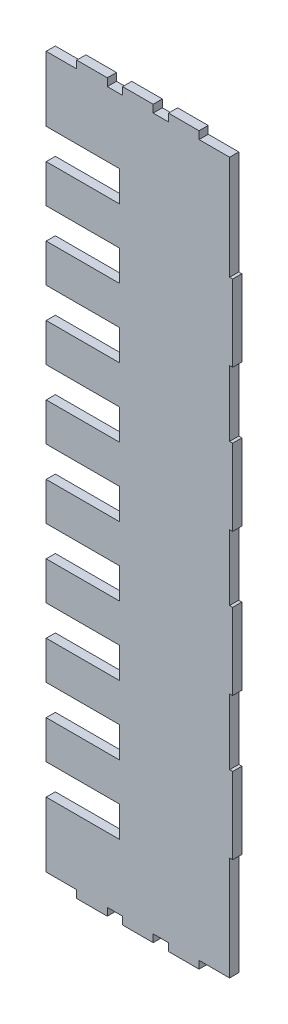
SolidWorks part; units mm, degrees
ref_plane "Front Plane" through (0, 0, 0) normal (0, 0, 1) x (1, 0, 0)
ref_plane "Top Plane" through (0, 0, 0) normal (0, 1, 0) x (1, 0, 0)
ref_plane "Right Plane" through (0, 0, 0) normal (1, 0, 0) x (0, 0, -1)
sketch "Sketch1" plane through (0, 0, 0) normal (0, 0, 1) x (1, 0, 0)
  line L1 (-60, -232.5) -> (60, -232.5)
  line L2 (-60, -232.5) -> (-60, 232.5)
  line L3 (-60, 232.5) -> (60, 232.5)
  line L4 (60, -232.5) -> (60, 232.5)
  line L5 (0, 232.5) -> (0, -232.5) construction
  line L6 (-60, 0) -> (60, 0) construction
  point P0 (0, 0)
  dimension "D1" = 465
  dimension "D2" = 120
extrude "Boss-Extrude1" add sketch "Sketch1" along normal blind 6
sketch "Sketch2" plane through (0, 0, 6) normal (0, 0, 1) x (1, 0, 0)
  line L0 (-60, -232.5) -> (60, -232.5) construction
  line L1 (-60, 232.5) -> (-42, 232.5)
  line L2 (-60, 232.5) -> (-60, -232.5)
  line L3 (-60, -232.5) -> (-42, -232.5)
  line L4 (-42, 232.5) -> (-42, -232.5)
  line L5 (-42, 232.5) -> (-42, 180)
  line L6 (-42, 190) -> (-42, 170)
  line L7 (-42, 170) -> (-42, 135)
  line L8 (-42, 190) -> (-12, 190)
  line L9 (-42, 190) -> (-42, 170)
  line L10 (-42, 170) -> (-12, 170)
  line L11 (-12, 190) -> (-12, 170)
  line L12 (-42, 145) -> (-42, 125)
  line L13 (-42, 100) -> (-42, 80)
  line L14 (-42, 55) -> (-42, 35)
  line L15 (-42, 10) -> (-42, -10)
  line L16 (-42, -35) -> (-42, -55)
  line L17 (-42, -80) -> (-42, -100)
  line L18 (-42, -125) -> (-42, -145)
  line L19 (-42, -170) -> (-42, -190)
  line L21 (-42, 145) -> (-12, 145)
  line L22 (-42, 145) -> (-42, 125)
  line L23 (-42, 125) -> (-12, 125)
  line L24 (-12, 145) -> (-12, 125)
  line L25 (-42, 100) -> (-12, 100)
  line L26 (-42, 100) -> (-42, 80)
  line L27 (-42, 80) -> (-12, 80)
  line L28 (-12, 100) -> (-12, 80)
  line L29 (-42, 55) -> (-12, 55)
  line L30 (-42, 55) -> (-42, 35)
  line L31 (-42, 35) -> (-12, 35)
  line L32 (-12, 55) -> (-12, 35)
  line L33 (-42, 10) -> (-12, 10)
  line L34 (-42, 10) -> (-42, -10)
  line L35 (-42, -10) -> (-12, -10)
  line L36 (-12, 10) -> (-12, -10)
  line L37 (-42, -35) -> (-12, -35)
  line L38 (-42, -35) -> (-42, -55)
  line L39 (-42, -55) -> (-12, -55)
  line L40 (-12, -35) -> (-12, -55)
  line L41 (-42, -80) -> (-12, -80)
  line L42 (-42, -80) -> (-42, -100)
  line L43 (-42, -100) -> (-12, -100)
  line L44 (-12, -80) -> (-12, -100)
  line L45 (-42, -125) -> (-12, -125)
  line L46 (-42, -125) -> (-42, -145)
  line L47 (-42, -145) -> (-12, -145)
  line L48 (-12, -125) -> (-12, -145)
  line L49 (-42, -170) -> (-12, -170)
  line L50 (-42, -170) -> (-42, -190)
  line L51 (-42, -190) -> (-12, -190)
  line L52 (-12, -170) -> (-12, -190)
  point P9 (-42, 180)
  point P12 (-42, 90)
  point P14 (-42, 45)
  point P15 (-42, 0)
  point P16 (-42, -45)
  point P17 (-42, -90)
  point P18 (-42, -135)
  point P19 (-42, -180)
  point P20 (-42, -232.5)
  point P24 (-42, 135)
  point P27 (-42, 90)
  point P30 (-42, 45)
  point P33 (-42, 0)
  point P36 (-42, -45)
  point P39 (-42, -90)
  point P42 (-42, -135)
  point P45 (-42, -180)
  dimension "D1" = 465
  dimension "D2" = 18
  dimension "D3" = 52.5
  dimension "D4" = 20
  dimension "D5" = 30
  dimension "D6" = 45
  dimension "D7" = 45
  dimension "D8" = 45
  dimension "D9" = 45
  dimension "D10" = 45
  dimension "D11" = 45
  dimension "D12" = 45
  dimension "D13" = 45
  dimension "D14" = 52.5
  dimension "D15" = 20
  dimension "D16" = 20
  dimension "D17" = 20
  dimension "D18" = 20
  dimension "D19" = 20
  dimension "D20" = 20
  dimension "D21" = 20
  dimension "D22" = 20
extrude "Cut-Extrude1" cut sketch "Sketch2" against normal blind 8 contours L11 L8 L5 L4 L10 | L24 L21 L7 L4 L23 | L28 L25 L4 L27 | L32 L29 L4 L31 | L36 L33 L4 L35 | L40 L37 L4 L39 | L44 L41 L4 L43 | L48 L45 L4 L47 | L52 L49 L4 L51
sketch "Sketch4" plane through (0, 0, 6) normal (0, 0, 1) x (1, 0, 0)
  line L0 (60, 232.5) -> (-60, 232.5) construction
  line L1 (-40, 237.5) -> (-20, 237.5)
  line L2 (-40, 237.5) -> (-40, 227.5)
  line L3 (-40, 227.5) -> (-20, 227.5)
  line L4 (-20, 237.5) -> (-20, 227.5)
  line L5 (-30, 227.5) -> (-30, 237.5) construction
  line L6 (-40, 232.5) -> (-20, 232.5) construction
  line L7 (-60, -232.5) -> (60, -232.5) construction
  line L8 (-10, 237.5) -> (10, 237.5)
  line L9 (-10, 237.5) -> (-10, 227.5)
  line L10 (-10, 227.5) -> (10, 227.5)
  line L11 (10, 237.5) -> (10, 227.5)
  line L12 (0, 227.5) -> (0, 237.5) construction
  line L13 (-10, 232.5) -> (10, 232.5) construction
  line L14 (40, 237.5) -> (20, 237.5)
  line L15 (40, 237.5) -> (40, 227.5)
  line L16 (40, 227.5) -> (20, 227.5)
  line L17 (20, 237.5) -> (20, 227.5)
  line L18 (30, 227.5) -> (30, 237.5) construction
  line L19 (40, 232.5) -> (20, 232.5) construction
  line L20 (-40, -227.5) -> (-20, -227.5)
  line L21 (-40, -227.5) -> (-40, -237.5)
  line L22 (-40, -237.5) -> (-20, -237.5)
  line L23 (-20, -227.5) -> (-20, -237.5)
  line L24 (-30, -237.5) -> (-30, -227.5) construction
  line L25 (-40, -232.5) -> (-20, -232.5) construction
  line L26 (60, -232.5) -> (60, 232.5) construction
  line L27 (-10, -227.5) -> (10, -227.5)
  line L28 (-10, -227.5) -> (-10, -237.5)
  line L29 (-10, -237.5) -> (10, -237.5)
  line L30 (10, -227.5) -> (10, -237.5)
  line L31 (0, -237.5) -> (0, -227.5) construction
  line L32 (-10, -232.5) -> (10, -232.5) construction
  line L33 (20, -227.5) -> (40, -227.5)
  line L34 (20, -227.5) -> (20, -237.5)
  line L35 (20, -237.5) -> (40, -237.5)
  line L36 (40, -227.5) -> (40, -237.5)
  line L37 (30, -237.5) -> (30, -227.5) construction
  line L38 (20, -232.5) -> (40, -232.5) construction
  line L39 (58, 164.5) -> (62, 164.5)
  line L40 (58, 164.5) -> (58, 114.5)
  line L41 (58, 114.5) -> (62, 114.5)
  line L42 (62, 164.5) -> (62, 114.5)
  line L43 (60, 114.5) -> (60, 164.5) construction
  line L44 (58, 139.5) -> (62, 139.5) construction
  line L46 (58, 71.5) -> (62, 71.5)
  line L47 (58, 71.5) -> (58, 21.5)
  line L48 (58, 21.5) -> (62, 21.5)
  line L49 (62, 71.5) -> (62, 21.5)
  line L50 (60, 21.5) -> (60, 71.5) construction
  line L51 (58, 46.5) -> (62, 46.5) construction
  line L52 (58, -71.5) -> (62, -71.5)
  line L53 (58, -71.5) -> (58, -21.5)
  line L54 (58, -21.5) -> (62, -21.5)
  line L55 (62, -71.5) -> (62, -21.5)
  line L56 (60, -21.5) -> (60, -71.5) construction
  line L57 (58, -46.5) -> (62, -46.5) construction
  line L58 (58, -114.5) -> (62, -114.5)
  line L59 (58, -114.5) -> (58, -164.5)
  line L60 (58, -164.5) -> (62, -164.5)
  line L61 (62, -114.5) -> (62, -164.5)
  line L62 (60, -164.5) -> (60, -114.5) construction
  line L63 (58, -139.5) -> (62, -139.5) construction
  point P0 (-30, 232.5)
  point P6 (0, 232.5)
  point P10 (30, 232.5)
  point P14 (-30, -232.5)
  point P20 (0, -232.5)
  point P24 (30, -232.5)
  point P28 (60, 139.5)
  point P34 (60, 46.5)
  point P38 (60, -46.5)
  point P42 (60, -139.5)
  dimension "D1" = 30
  dimension "D2" = 60
  dimension "D3" = 90
  dimension "D4" = 20
  dimension "D5" = 20
  dimension "D6" = 20
  dimension "D7" = 10
  dimension "D8" = 10
  dimension "D9" = 10
  dimension "D10" = 30
  dimension "D11" = 60
  dimension "D12" = 90
  dimension "D13" = 20
  dimension "D14" = 20
  dimension "D15" = 20
  dimension "D16" = 10
  dimension "D17" = 10
  dimension "D18" = 10
  dimension "D19" = 93
  dimension "D20" = 93
  dimension "D21" = 93
  dimension "D22" = 93
  dimension "D23" = 4
  dimension "D24" = 4
  dimension "D25" = 4
  dimension "D26" = 4
  dimension "D27" = 50
  dimension "D28" = 50
  dimension "D29" = 50
  dimension "D30" = 50
extrude "Boss-Extrude2" add sketch "Sketch4" against normal blind 6
sketch "Sketch5" plane through (0, 0, 6) normal (0, 0, 1) x (1, 0, 0)
  line L0 (-60, 232.5) -> (-60, -232.5) construction
  line L1 (-42, 190) -> (-60, 190)
  line L2 (-42, 190) -> (-42, 170)
  line L3 (-42, 170) -> (-60, 170)
  line L4 (-60, 190) -> (-60, 170)
  line L6 (-42, 145) -> (-60, 145)
  line L7 (-42, 145) -> (-42, 125)
  line L8 (-42, 125) -> (-60, 125)
  line L9 (-60, 145) -> (-60, 125)
  line L10 (-42, 100) -> (-60, 100)
  line L11 (-42, 100) -> (-42, 80)
  line L12 (-42, 80) -> (-60, 80)
  line L13 (-60, 100) -> (-60, 80)
  line L14 (-42, 55) -> (-60, 55)
  line L15 (-42, 55) -> (-42, 35)
  line L16 (-42, 35) -> (-60, 35)
  line L17 (-60, 55) -> (-60, 35)
  line L18 (-42, 10) -> (-60, 10)
  line L19 (-42, 10) -> (-42, -10)
  line L20 (-42, -10) -> (-60, -10)
  line L21 (-60, 10) -> (-60, -10)
  line L22 (-42, -35) -> (-60, -35)
  line L23 (-42, -35) -> (-42, -55)
  line L24 (-42, -55) -> (-60, -55)
  line L25 (-60, -35) -> (-60, -55)
  line L26 (-42, -80) -> (-60, -80)
  line L27 (-42, -80) -> (-42, -100)
  line L28 (-42, -100) -> (-60, -100)
  line L29 (-60, -80) -> (-60, -100)
  line L30 (-42, -125) -> (-60, -125)
  line L31 (-42, -125) -> (-42, -145)
  line L32 (-42, -145) -> (-60, -145)
  line L33 (-60, -125) -> (-60, -145)
  line L34 (-42, -170) -> (-60, -170)
  line L35 (-42, -170) -> (-42, -190)
  line L36 (-42, -190) -> (-60, -190)
  line L37 (-60, -170) -> (-60, -190)
extrude "Cut-Extrude2" cut sketch "Sketch5" against normal blind 10
